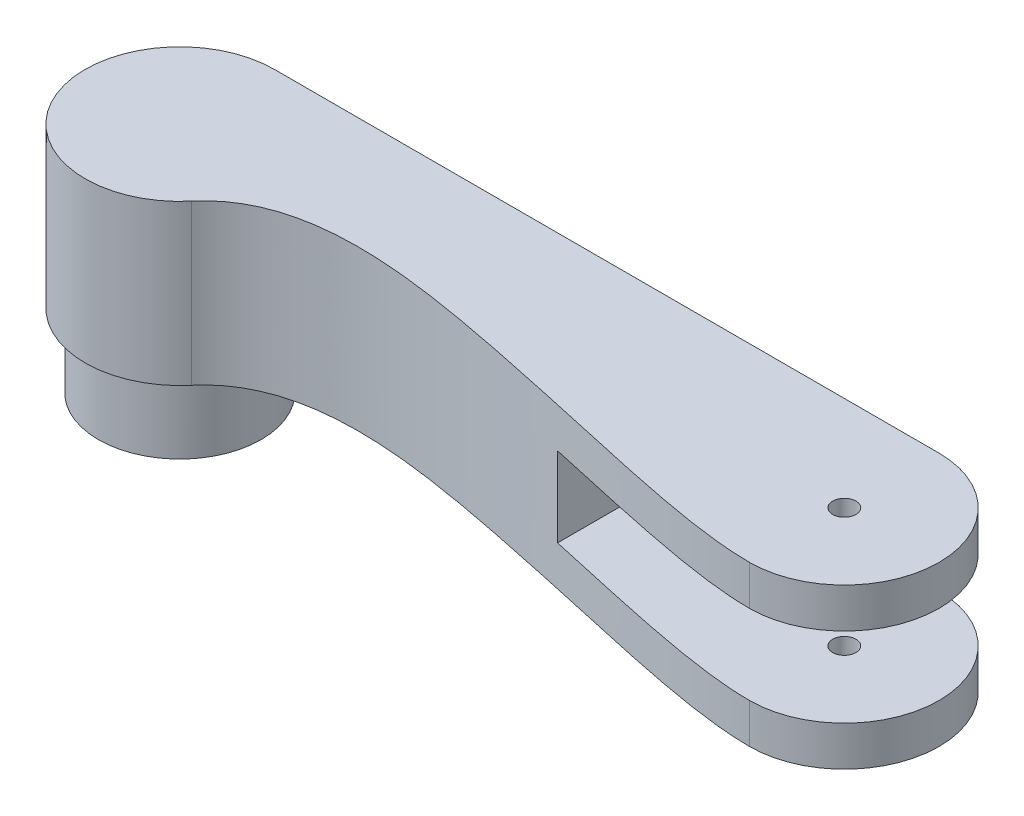
SolidWorks part; units mm, degrees
ref_plane "Front Plane" through (0, 0, 0) normal (0, 0, 1) x (1, 0, 0)
ref_plane "Top Plane" through (0, 0, 0) normal (0, 1, 0) x (1, 0, 0)
ref_plane "Right Plane" through (0, 0, 0) normal (1, 0, 0) x (0, 0, -1)
sketch "Sketch1" plane through (0, 0, 0) normal (0, 1, 0) x (1, 0, 0)
  line L0 (-50, 0) -> (50, 0) construction
  line L1 (-50, 14.25) -> (50, 14.25)
  line L2 (-50, -14.25) -> (50, -14.25)
  arc A0 (-50, 14.25) -> (-50, -14.25) centre (-50, 0) ccw
  arc A1 (50, -14.25) -> (50, 14.25) centre (50, 0) ccw
  point P3 (0, 0)
  dimension "D1" = 14.25
  dimension "D2" = 100
extrude "Boss-Extrude1" add sketch "Sketch1" along normal blind 6
sketch "Sketch3" plane through (0, 0, 0) normal (0, -1, 0) x (1, 0, 0)
  circle A0 centre (50, 0) radius 1.75
  dimension "D1" = 3.5
extrude "Cut-Extrude2" cut sketch "Sketch3" against normal through all
sketch "Sketch4" plane through (0, 6, 0) normal (0, 1, 0) x (1, 0, 0)
  line L0 (-50, 14.25) -> (15, 14.25)
  line L1 (-50, 14.25) -> (50, 14.25) construction
  line L2 (15, 14.25) -> (15, -14.25)
  line L3 (-50, -14.25) -> (50, -14.25) construction
  line L4 (15, -14.25) -> (-50, -14.25)
  arc A0 (-50, 14.25) -> (-50, -14.25) centre (-50, 0) ccw
  arc A1 (-50, 14.25) -> (-50, -14.25) centre (-50, 0) ccw construction
  dimension "D1" = 65
extrude "Boss-Extrude2" add sketch "Sketch4" along normal blind 12
sketch "Sketch5" plane through (0, 18, 0) normal (0, 1, 0) x (1, 0, 0)
  line L0 (-50, 0) -> (50, 0) construction
  line L1 (-50, 14.25) -> (50, 14.25)
  line L2 (-50, -14.25) -> (50, -14.25)
  arc A0 (-50, 14.25) -> (-50, -14.25) centre (-50, 0) ccw
  arc A1 (50, -14.25) -> (50, 14.25) centre (50, 0) ccw
  point P4 (0, 0)
  dimension "D1" = 14.25
extrude "Boss-Extrude3" add sketch "Sketch5" along normal blind 6
sketch "Sketch6" plane through (0, 24, 0) normal (0, 1, 0) x (1, 0, 0)
  circle A0 centre (50, 0) radius 1.75
  dimension "D1" = 3.5
extrude "Cut-Extrude3" cut sketch "Sketch6" against normal up to next
sketch "Sketch7" plane through (0, 24, 0) normal (0, 1, 0) x (1, 0, 0)
  line L0 (0, -13.2) -> (0, 13.2) construction
  line L1 (-50, -14.25) -> (50, -14.25)
  circle A0 centre (-50, 0) radius 14.25
  circle A1 centre (50, 0) radius 14.25
  spline S0 degree 3 poles (-39.0732, -9.1469) (-31.5141, -0.117) (5.4387, -4.6452) (38.6975, -14.25) (50, -14.25) knots 0 0 0 0 0.435908 1 1 1 1
  line M5 (-50, -14.25) -> (50, -14.25)
extrude "Cut-Extrude4" cut sketch "Sketch7" against normal up to next contours S0 A0 M5
sketch "Sketch8" plane through (0, 0, 0) normal (0, -1, 0) x (1, 0, 0)
  circle A1 centre (-50, 0) radius 12.25
  dimension "D1" = 24.5
extrude "Boss-Extrude4" add sketch "Sketch8" along normal blind 11
sketch "Sketch9" plane through (0, -11, 0) normal (0, -1, 0) x (1, 0, 0)
  circle A0 centre (-50, 0) radius 6.75 construction
  circle A1 centre (-50, 6.75) radius 2.55
  circle A2 centre (-50, -6.75) radius 2.55
  arc A3 (-50, 14.25) -> (-50, -14.25) centre (-50, 0) ccw construction
  circle A4 centre (-50, 0) radius 3
  point P6 (-50, 0)
  dimension "D1" = 13.5
  dimension "D2" = 5.1
  dimension "D3" = 6
extrude "Cut-Extrude5" cut sketch "Sketch9" against normal blind 6
equation "\"Length\"= 100mm"
equation "\"Radius\"= 14.25mm"
equation "\"Thick\"= 12mm"
equation "\"D1@Sketch1\"= \"Radius\""
equation "\"D2@Sketch1\" = \"Length\""
equation "\"D1@Boss-Extrude1\"= \"Thick\""
equation "\"D1@Sketch4\"=\"Length\"*0.65"
equation "\"D1@Sketch5\"=\"Radius\""
equation "\"D1@Boss-Extrude2\"=\"Thick\""
equation "\"D1@Boss-Extrude4\"=\"Thick\"-1"
